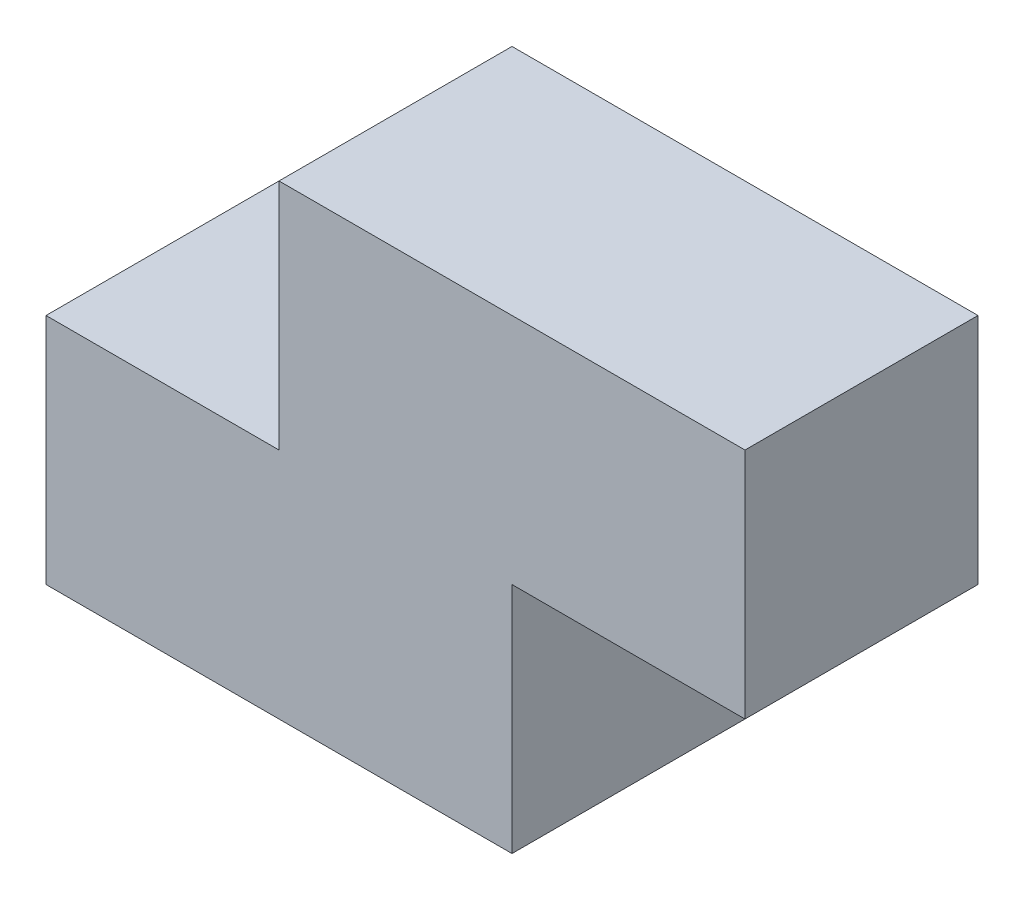
SolidWorks part; units mm, degrees
ref_plane "Plan de face" through (0, 0, 0) normal (0, 0, 1) x (1, 0, 0)
ref_plane "Plan de dessus" through (0, 0, 0) normal (0, 1, 0) x (1, 0, 0)
ref_plane "Plan de droite" through (0, 0, 0) normal (1, 0, 0) x (0, 0, -1)
sketch "Esquisse1" plane through (0, 0, 0) normal (0, 0, 1) x (1, 0, 0)
  line L0 (0, 0) -> (0, 10)
  line L1 (0, 10) -> (10, 10)
  line L2 (10, 10) -> (10, 20)
  line L3 (10, 20) -> (30, 20)
  line L4 (30, 20) -> (30, 10)
  line L5 (20, 10) -> (30, 10)
  line L6 (20, 10) -> (20, 0)
  line L7 (20, 0) -> (0, 0)
  dimension "D1" = 20
  dimension "D2" = 20
  dimension "D3" = 10
  dimension "D4" = 10
  dimension "D5" = 10
  dimension "D6" = 10
extrude "Boss.-Extru.1" add sketch "Esquisse1" against normal blind 10
